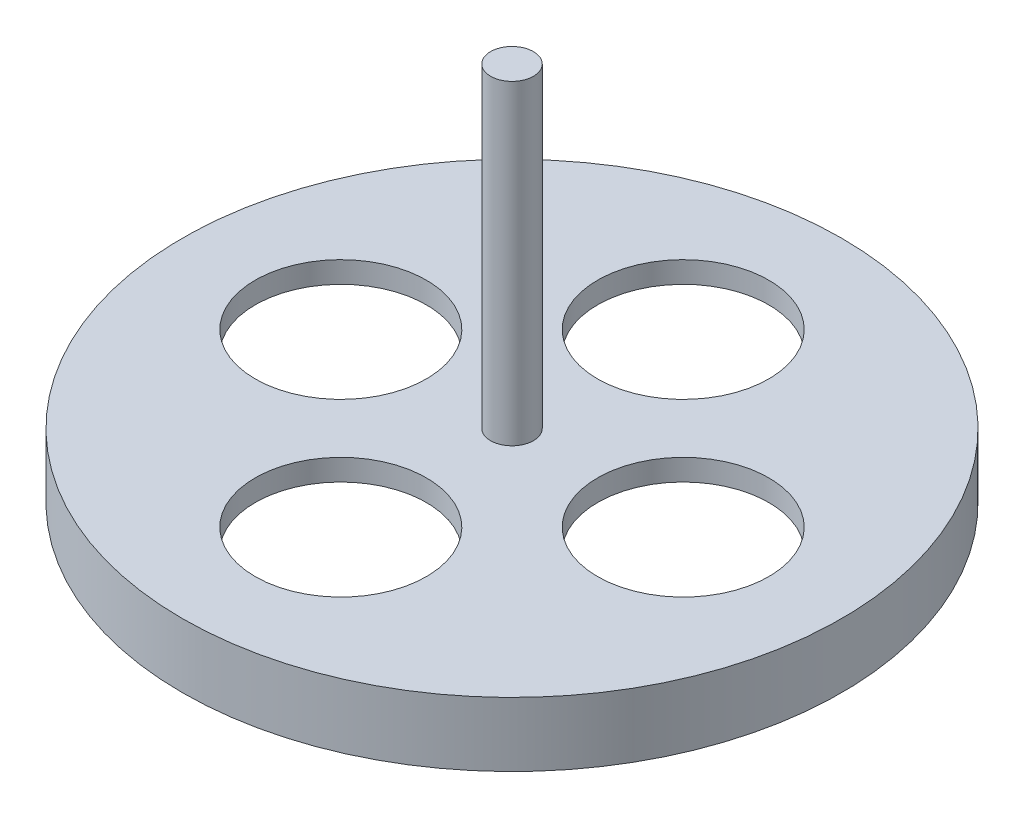
SolidWorks part; units mm, degrees
ref_plane "Front Plane" through (0, 0, 0) normal (0, 0, 1) x (1, 0, 0)
ref_plane "Top Plane" through (0, 0, 0) normal (0, 1, 0) x (1, 0, 0)
ref_plane "Right Plane" through (0, 0, 0) normal (1, 0, 0) x (0, 0, -1)
sketch "Sketch1" plane through (0, 0, 0) normal (0, 1, 0) x (1, 0, 0)
  circle A0 centre (0, 0) radius 45.72
  circle A1 centre (0, 0) radius 48.895
  dimension "D1" = 91.44
  dimension "D2" = 97.79
extrude "Boss-Extrude1" add sketch "Sketch1" along normal blind 6.35
sketch "Sketch2" plane through (0, 6.35, 0) normal (0, 1, 0) x (1, 0, 0)
  circle A0 centre (0, 0) radius 48.895
  circle A1 centre (0, 25.4) radius 12.7
  circle A2 centre (25.4, 0) radius 12.7
  circle A3 centre (0, -25.4) radius 12.7
  circle A4 centre (-25.4, 0) radius 12.7
  point P14 (0, 0)
  dimension "D2" = 25.4
  dimension "D1" = 25.4
  dimension "D3" = 4
extrude "Boss-Extrude2" add sketch "Sketch2" along normal blind 3.175
sketch "Sketch3" plane through (0, 9.525, 0) normal (0, 1, 0) x (1, 0, 0)
  circle A0 centre (0, 0) radius 3.175
  dimension "D1" = 6.35
extrude "Boss-Extrude3" add sketch "Sketch3" along normal blind 46.825
